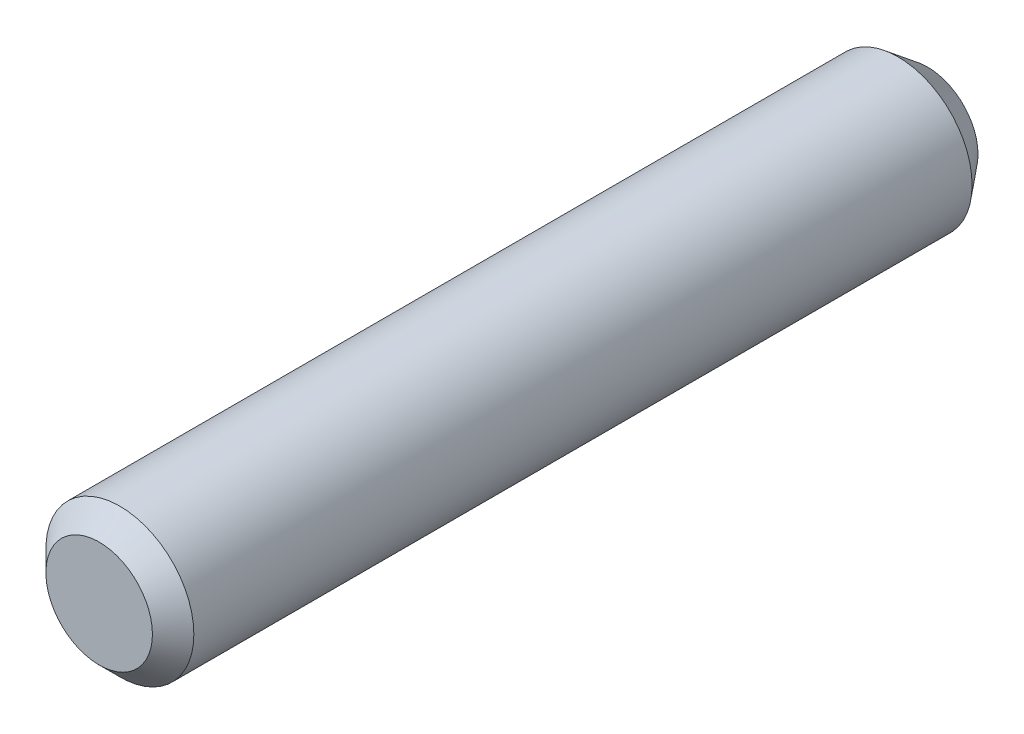
SolidWorks part; units mm, degrees
ref_plane "Plan de face" through (0, 0, 0) normal (0, 0, 1) x (1, 0, 0)
ref_plane "Plan de dessus" through (0, 0, 0) normal (0, 1, 0) x (1, 0, 0)
ref_plane "Plan de droite" through (0, 0, 0) normal (1, 0, 0) x (0, 0, -1)
sketch "Sketch1" plane through (0, 0, 0) normal (0, 0, 1) x (1, 0, 0)
  circle A0 centre (0, 0) radius 1.25
  dimension "D1" = 2.5
extrude "Boss-Extrude1" add sketch "Sketch1" along normal blind 14
chamfer "Chamfer1" distance 0.35 angle 45 1 edges at (1.25, 0, 14)
chamfer "Chamfer2" distance 0.4 distance2 0.5 1 edges at (1.25, 0, 0)
